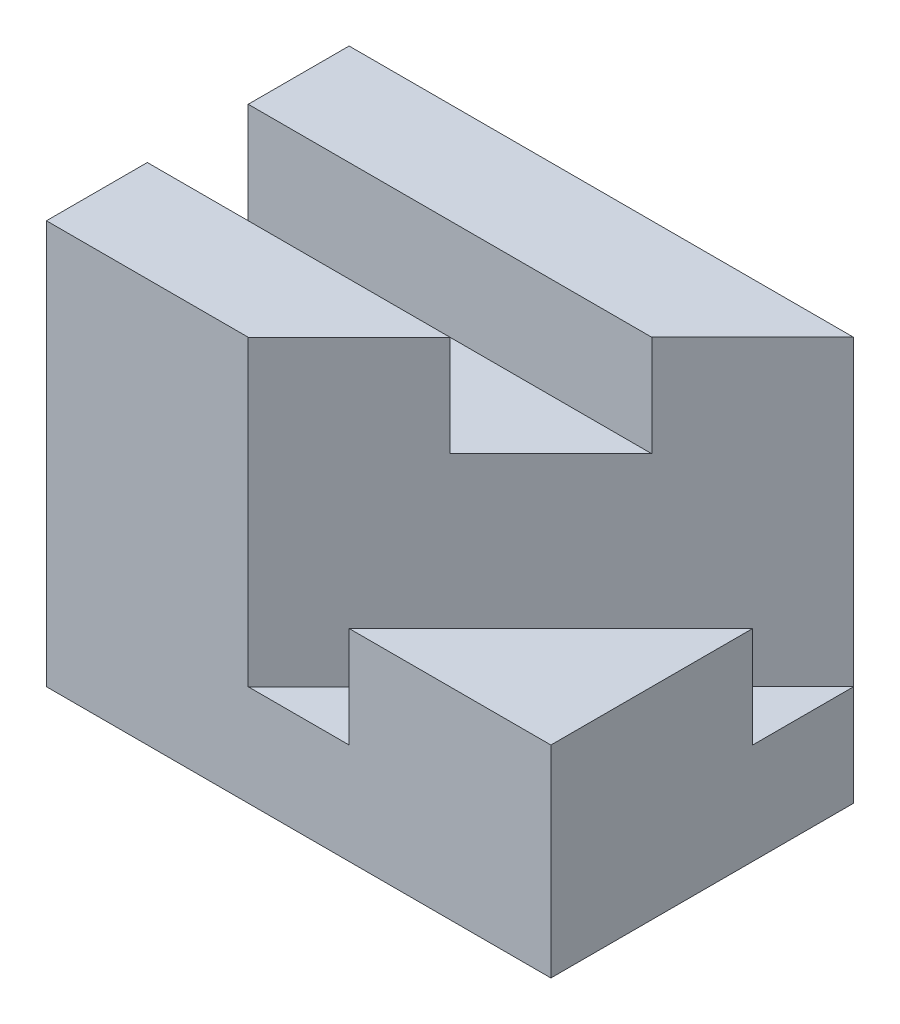
SolidWorks part; units mm, degrees
ref_plane "前基準面" through (0, 0, 0) normal (0, 0, 1) x (1, 0, 0)
ref_plane "上基準面" through (0, 0, 0) normal (0, 1, 0) x (1, 0, 0)
ref_plane "右基準面" through (0, 0, 0) normal (1, 0, 0) x (0, 0, -1)
sketch "草圖1" plane through (0, 0, 0) normal (0, 1, 0) x (1, 0, 0)
  line L0 (0, 0) -> (5, 0)
  line L1 (5, 0) -> (5, 3)
  line L2 (5, 3) -> (0, 3)
  line L3 (0, 3) -> (0, 0)
  dimension "D1" = 3
  dimension "D2" = 5
extrude "填料-伸長1" add sketch "草圖1" along normal blind 1
sketch "草圖2" plane through (0, 1, 0) normal (0, 1, 0) x (1, 0, 0)
  line L5 (5, 0) -> (5, 2)
  line L6 (5, 0) -> (5, 3) construction
  line L7 (5, 0) -> (3, 0)
  line L8 (0, 0) -> (5, 0) construction
  line L9 (3, 0) -> (5, 2)
  dimension "D1" = 2
  dimension "D2" = 2
extrude "填料-伸長2" add sketch "草圖2" along normal blind 1
sketch "草圖3" plane through (0, 1, 0) normal (0, 1, 0) x (1, 0, 0)
  line L0 (0, 0) -> (0, 3)
  line L1 (0, 3) -> (5, 3)
  line L2 (5, 3) -> (2, 0)
  line L3 (0, 0) -> (3, 0) construction
  line L4 (2, 0) -> (0, 0)
  dimension "D1" = 2
extrude "填料-伸長3" add sketch "草圖3" along normal blind 3
sketch "草圖4" plane through (0, 0, 0) normal (-1, 0, 0) x (0, 0, 1)
  line L1 (-3, 4) -> (0, 4) construction
  line L2 (-2, 4) -> (-2, 3)
  line L3 (-2, 3) -> (-1, 3)
  line L4 (-1, 3) -> (-1, 4)
  line L5 (-2, 4) -> (-1, 4)
  dimension "D2" = 1
  dimension "D3" = 1
extrude "除料-伸長1" cut sketch "草圖4" against normal blind 6
